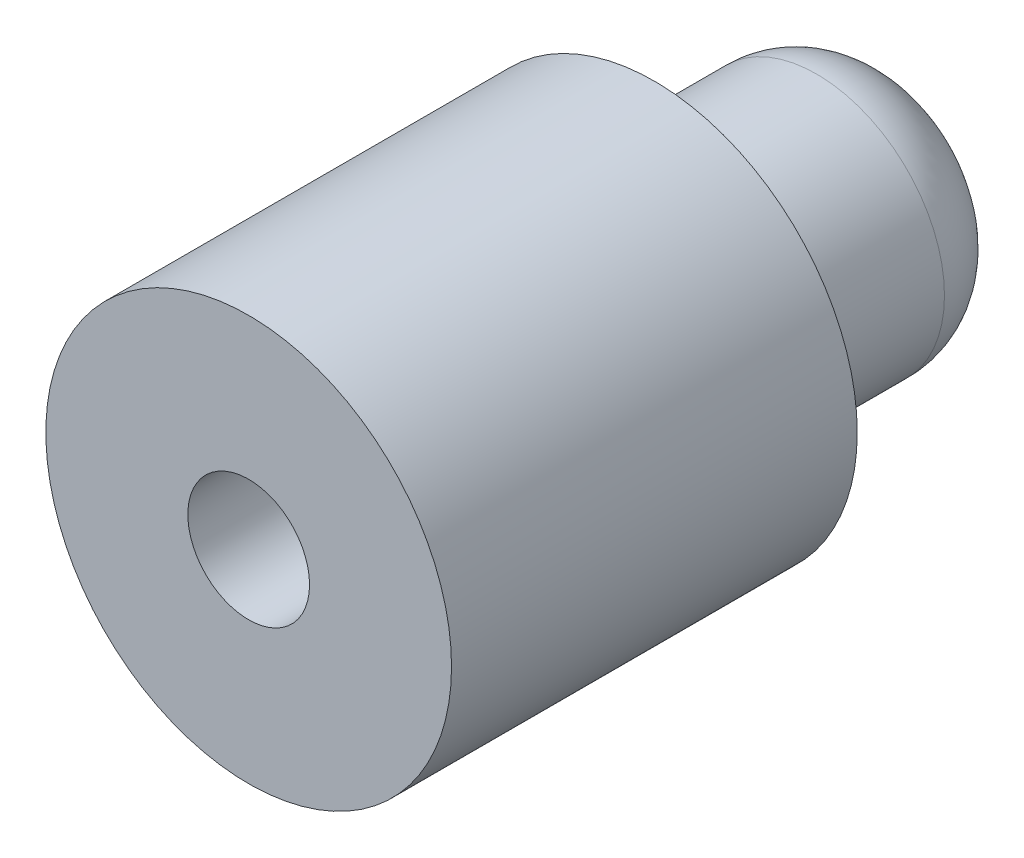
SolidWorks part; units mm, degrees
material "ABS"
ref_plane "Plan de face" through (0, 0, 0) normal (0, 0, 1) x (1, 0, 0)
ref_plane "Plan de dessus" through (0, 0, 0) normal (0, 1, 0) x (1, 0, 0)
ref_plane "Plan de droite" through (0, 0, 0) normal (1, 0, 0) x (0, 0, -1)
sketch "Esquisse1" plane through (0, 0, 0) normal (0, 0, 1) x (1, 0, 0)
  circle A0 centre (0, 0) radius 3.15
  dimension "D1" = 6.3
extrude "Boss.-Extru.1" add sketch "Esquisse1" along normal blind 6
sketch "Esquisse3" plane through (0, 0, 6) normal (0, 0, 1) x (1, 0, 0)
  circle A0 centre (0, 0) radius 5
  dimension "D1" = 10
extrude "Boss.-Extru.2" add sketch "Esquisse3" along normal blind 10
sketch "Esquisse4" plane through (0, 0, 16) normal (0, 0, 1) x (1, 0, 0)
  circle A0 centre (0, 0) radius 1.5
  dimension "D1" = 3
extrude "Enlèv. mat.-Extru.1" cut sketch "Esquisse4" against normal blind 10
fillet "Congé1" radius 2 1 edges at (3.15, 0, 0)
